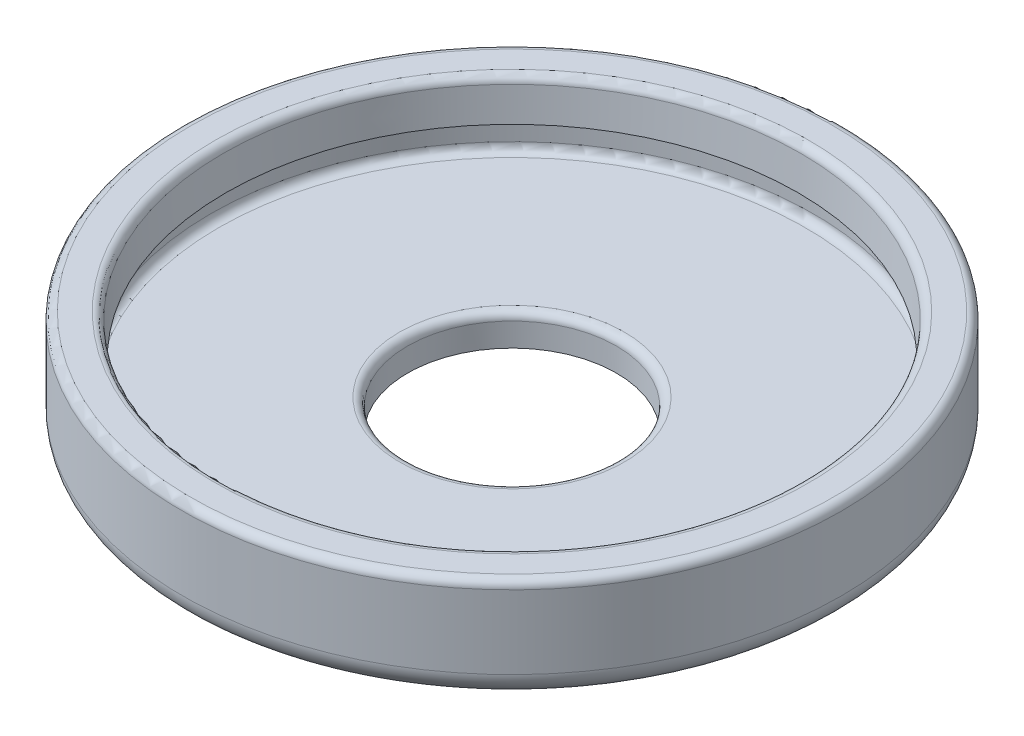
SolidWorks part; units mm, degrees
material "6061-T6 (SS)"
ref_plane "Front Plane" through (0, 0, 0) normal (0, 0, 1) x (1, 0, 0)
ref_plane "Top Plane" through (0, 0, 0) normal (0, 1, 0) x (1, 0, 0)
ref_plane "Right Plane" through (0, 0, 0) normal (1, 0, 0) x (0, 0, -1)
sketch "Sketch1" plane through (0, 0, 0) normal (0, 0, 1) x (1, 0, 0)
  line L0 (0, -34.2214) -> (0, 1676.8503) construction
  line L1 (-34.2214, 0) -> (1676.8503, 0) construction
  line L2 (1.651, 0) -> (5.207, 0)
  line L3 (5.207, 0) -> (5.207, 1.6676)
  line L4 (5.207, 1.6676) -> (4.572, 1.6676)
  line L5 (4.572, 1.6676) -> (4.5212, 1.0326)
  line L6 (4.5212, 1.0326) -> (4.7625, 1.0326)
  line L7 (4.7625, 1.0326) -> (4.7625, 0.4975)
  line L8 (4.7625, 0.4975) -> (1.651, 0.4975)
  line L9 (1.651, 0.4975) -> (1.651, 0)
  dimension "D1" = 1.651
  dimension "D2" = 5.207
  dimension "D3" = 1.6676
  dimension "D4" = 9.525
  dimension "D5" = 9.0424
  dimension "D6" = 0.635
  dimension "D7" = 0.4975
  dimension "D8" = 0.635
revolve "Revolve1" add sketch "Sketch1" angle 360 about L0
fillet "Fillet1" radius 0.381 1 edges at (5.207, 0, 0)
fillet "Fillet2" radius 0.127 4 edges at (4.7625, 0.4975, 0) (1.651, 0.4975, 0) (4.572, 1.6676, 0) (5.207, 1.6676, 0)
equation "\"D8@Sketch1\"=\"D6@Sketch1\""
